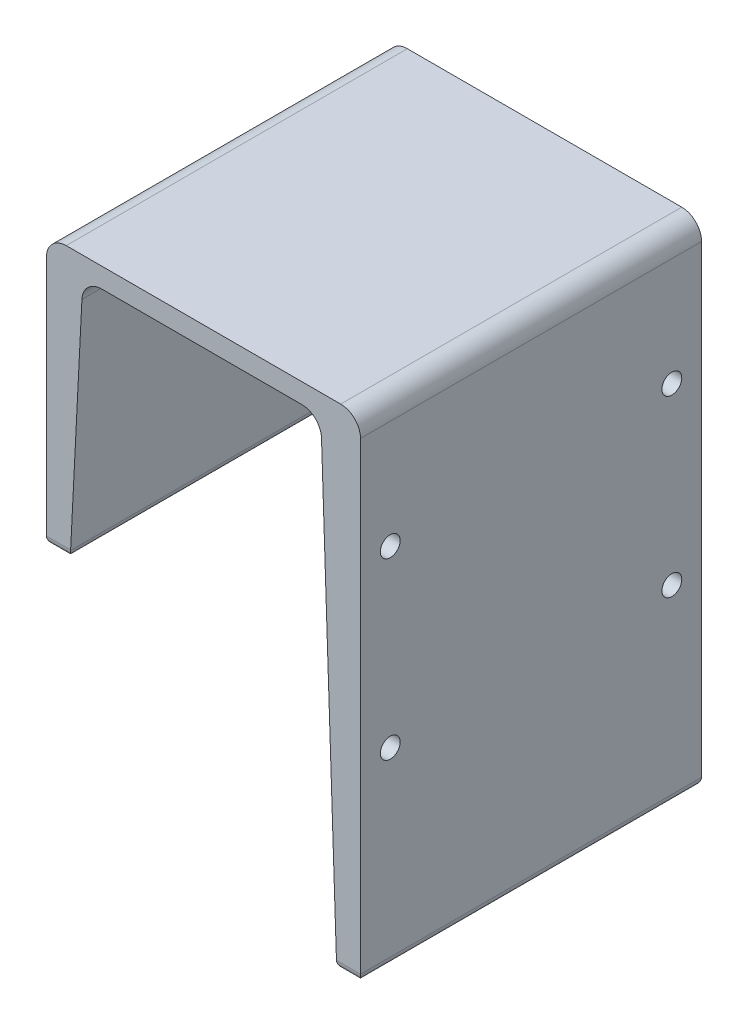
SolidWorks part; units mm, degrees
ref_plane "Front Plane" through (0, 0, 0) normal (0, 0, 1) x (1, 0, 0)
ref_plane "Top Plane" through (0, 0, 0) normal (0, 1, 0) x (1, 0, 0)
ref_plane "Right Plane" through (0, 0, 0) normal (1, 0, 0) x (0, 0, -1)
sketch "Sketch1" plane through (0, 0, 0) normal (0, 0, 1) x (1, 0, 0)
  line L0 (0, 0) -> (1.6, 31.4589)
  line L1 (1.6, 31.4589) -> (31.6, 31.4589)
  line L2 (31.6, 31.4589) -> (33.6, -28.0411)
  line L3 (0, 0) -> (-3, 0)
  line L4 (-3, 0) -> (-3, 33.9589)
  line L5 (-3, 33.9589) -> (36.6, 33.9589)
  line L6 (36.6, 33.9589) -> (36.6, -28.0411)
  line L7 (36.6, -28.0411) -> (33.6, -28.0411)
  dimension "D1" = 1.6
  dimension "D2" = 2
  dimension "D3" = 30
  dimension "D4" = 62
  dimension "D5" = 2.5
  dimension "D6" = 33.9589
extrude "Boss-Extrude1" add sketch "Sketch1" against normal blind 43
ref_plane "Plane1" through (0, 0, -20) normal (0, 0, 1) x (1, 0, 0)
sketch "Sketch2" plane through (36.6, 0, 0) normal (1, 0, 0) x (0, 0, -1)
  line L0 (21.5, 33.9589) -> (21.5, -28.0411) construction
  line L1 (43, 33.9589) -> (0, 33.9589) construction
  line L2 (43, -28.0411) -> (0, -28.0411) construction
  line L3 (21.5, 33.9589) -> (43, 33.9589) construction
  circle A0 centre (39.25, 17.8191) radius 1.25
  circle A2 centre (39.25, -4.1809) radius 1.25
  circle A3 centre (3.75, -4.1809) radius 1.25
  circle A4 centre (3.75, 17.8191) radius 1.25
  point P16 (0, 0)
  point P17 (0, 0)
  point P18 (0, 0)
  dimension "D2" = 22
  dimension "D1" = 17.75
extrude "Cut-Extrude1" cut sketch "Sketch2" against normal up to next
fillet "Fillet1" radius 2.5 2 edges at (1.6, 31.4589, -21.5) (31.6, 31.4589, -21.5)
fillet "Fillet2" radius 2.5 2 edges at (-3, 33.9589, -21.5) (36.6, 33.9589, -21.5)
fillet "Fillet3" radius 1 4 edges at (-1.5, 0, -43) (-3, 0, -21.5) (0, 0, -21.5) (-1.5, 0, 0)
fillet "Fillet4" radius 1 4 edges at (35.1, -28.0411, -43) (35.1, -28.0411, 0) (33.6, -28.0411, -21.5) (36.6, -28.0411, -21.5)
